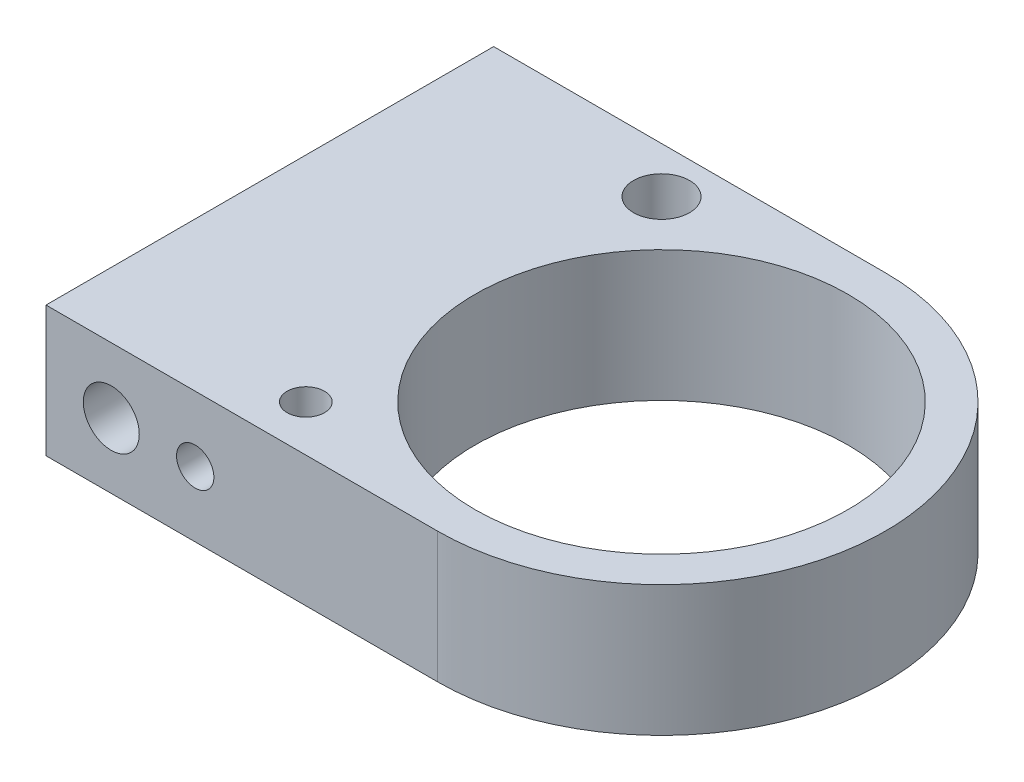
SolidWorks part; units mm, degrees
ref_plane "Спереди" through (0, 0, 0) normal (0, 0, 1) x (1, 0, 0)
ref_plane "Сверху" through (0, 0, 0) normal (0, 1, 0) x (1, 0, 0)
ref_plane "Справа" through (0, 0, 0) normal (1, 0, 0) x (0, 0, -1)
sketch "Эскиз1" plane through (0, 0, 0) normal (0, 1, 0) x (1, 0, 0)
  line L0 (-6, -6) -> (-6, 6)
  line L1 (-6, 6) -> (-7, 6)
  line L2 (-7, 6) -> (-7, -6)
  line L3 (-7, -6) -> (-6, -6)
  line L4 (-7, 6) -> (-8, 6)
  line L5 (-8, 6) -> (-9.5, 6)
  line L6 (-9.5, 6) -> (-10.5, 6)
  line L7 (-10.5, 6) -> (-10.5, -6)
  line L8 (-10.5, -6) -> (-7, -6)
  line L9 (-9.5, 6) -> (-9.5, -6)
  line L10 (-8, 6) -> (-8, -6)
  line L11 (-6, 6) -> (0, 6)
  line L12 (-6, -6) -> (0, -6)
  circle A0 centre (0, 0) radius 5
  circle A1 centre (0, 0) radius 6
  point P7 (-6, 0)
extrude "Бобышка-Вытянуть1" add sketch "Эскиз1" along normal blind 3.5 contours L9 L6 L7 L8 | L10 L5 L9 L8 | L4 L10 L8 L2 | L2 L3 L0 L1 | A1 L0 L12 | A1 A0 | A1 L11 L0
sketch "Эскиз2" plane through (0, 0, 6) normal (0, 0, 1) x (1, 0, 0)
  line L0 (-10.5, 1.75) -> (-9.5, 1.75) construction
  line L1 (-10.5, 3.5) -> (-10.5, 0) construction
  line L2 (-8, 1.75) -> (-7, 1.75) construction
  circle A1 centre (-8.75, 1.75) radius 0.75
  circle A3 centre (-6.5, 1.75) radius 0.5
extrude "Вырез-Вытянуть1" cut sketch "Эскиз2" against normal through all and the other way through all
sketch "Эскиз3" plane through (0, 3.5, 0) normal (0, 1, 0) x (1, 0, 0)
  line L0 (0, 0) -> (-10.5, 0) construction
  line L1 (-6, 6) -> (-3.5355, 3.5355) construction
  line L2 (-10.5, 6) -> (-10.5, -6) construction
  line L3 (-6, -6) -> (-3.5355, -3.5355) construction
  circle A0 centre (0, 0) radius 5 construction
  circle A1 centre (-4.7678, 4.7678) radius 0.75
  circle A2 centre (-4.7678, -4.7678) radius 0.5
extrude "Вырез-Вытянуть2" cut sketch "Эскиз3" against normal blind 3.5
